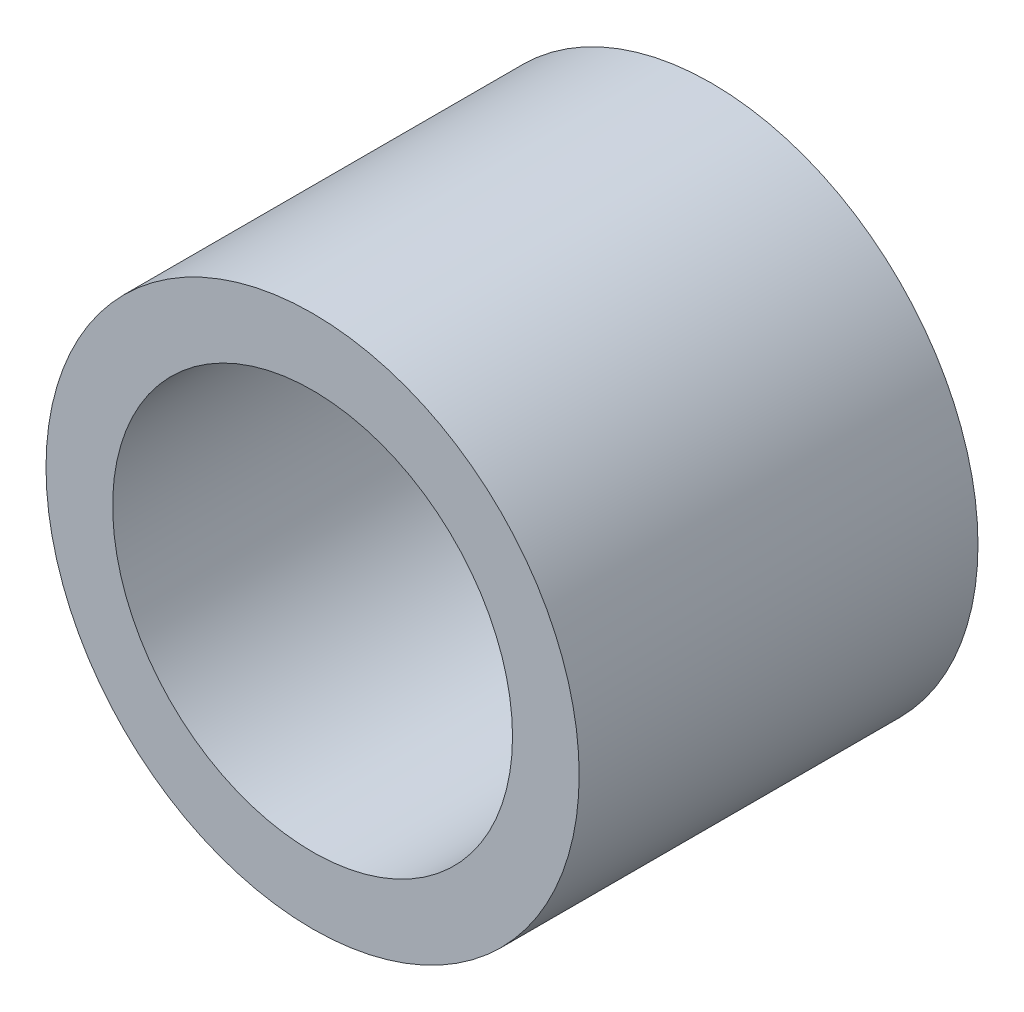
SolidWorks part; units mm, degrees
ref_plane "Front Plane" through (0, 0, 0) normal (0, 0, 1) x (1, 0, 0)
ref_plane "Top Plane" through (0, 0, 0) normal (0, 1, 0) x (1, 0, 0)
ref_plane "Right Plane" through (0, 0, 0) normal (1, 0, 0) x (0, 0, -1)
sketch "Sketch1" plane through (0, 0, 0) normal (0, 0, 1) x (1, 0, 0)
  circle A0 centre (0, 0) radius 12.7
  circle A1 centre (0, 0) radius 9.525
  dimension "D1" = 25.4
  dimension "D2" = 19.05
extrude "Boss-Extrude1" add sketch "Sketch1" along normal mid plane 19
